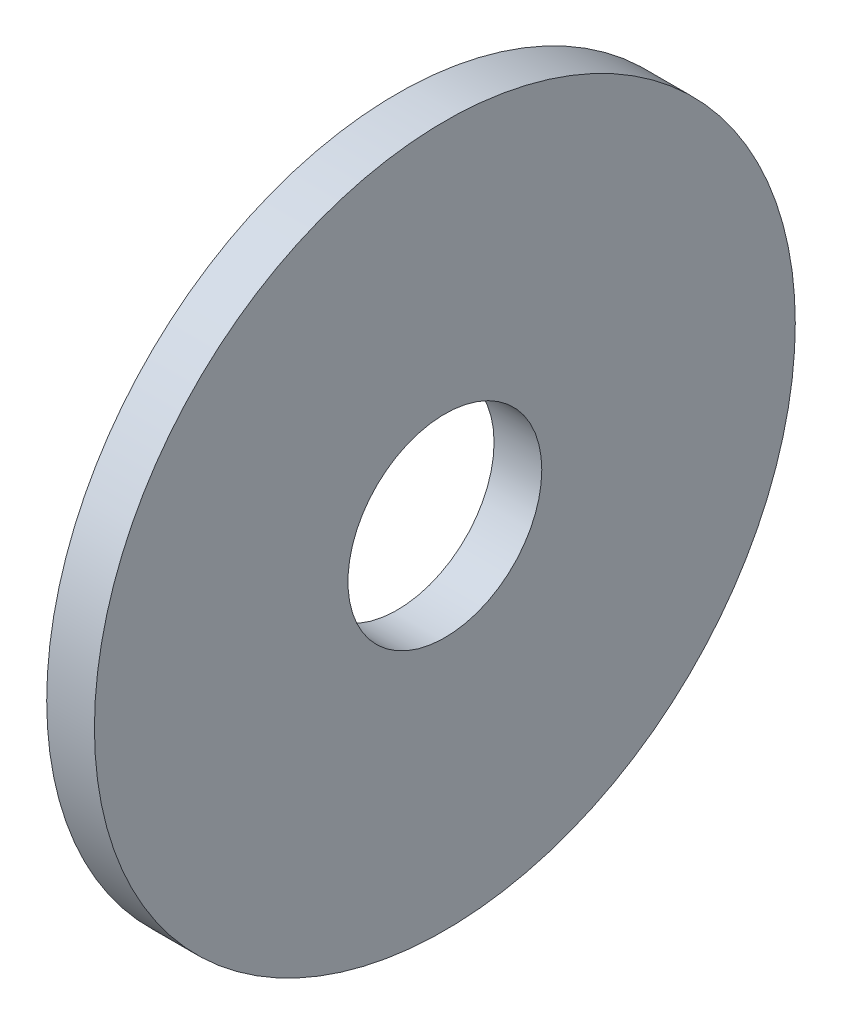
SolidWorks part; units mm, degrees
ref_plane "Front Plane" through (0, 0, 0) normal (0, 0, 1) x (1, 0, 0)
ref_plane "Top Plane" through (0, 0, 0) normal (0, 1, 0) x (1, 0, 0)
ref_plane "Right Plane" through (0, 0, 0) normal (1, 0, 0) x (0, 0, -1)
sketch "Sketch2" plane through (0, 0, 0) normal (1, 0, 0) x (0, 0, -1)
  circle A0 centre (0, 0) radius 9.3266
  circle A1 centre (0, 0) radius 2.5797
extrude "Boss-Extrude1" add sketch "Sketch2" along normal blind 1.27
